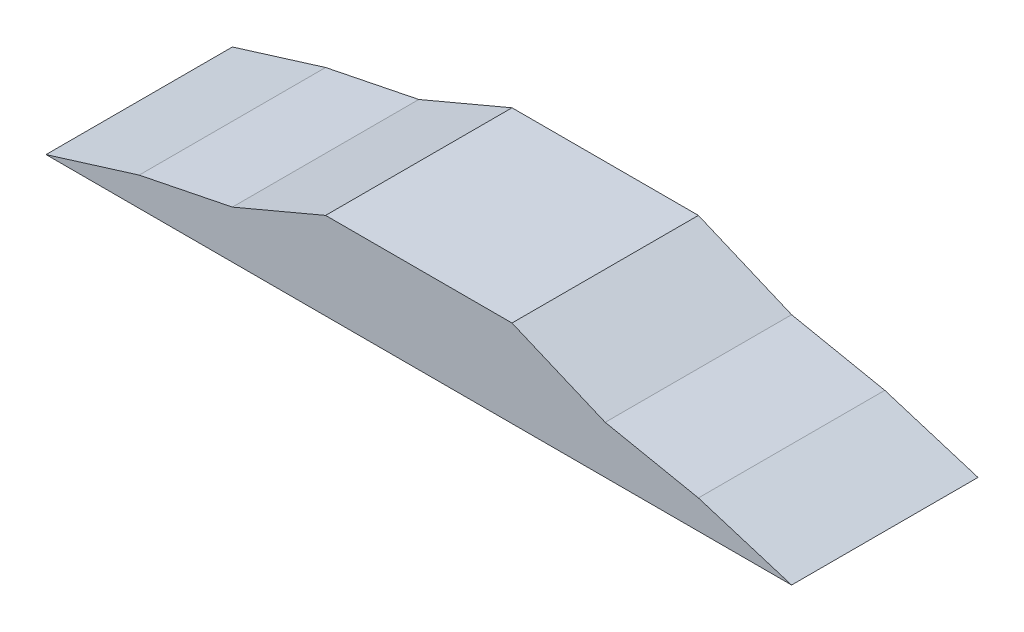
SolidWorks part; units mm, degrees
ref_plane "前视基准面" through (0, 0, 0) normal (0, 0, 1) x (1, 0, 0)
ref_plane "上视基准面" through (0, 0, 0) normal (0, 1, 0) x (1, 0, 0)
ref_plane "右视基准面" through (0, 0, 0) normal (1, 0, 0) x (0, 0, -1)
other "Configuration Table"
sketch "草图1" plane through (0, 0, 0) normal (0, 0, 1) x (1, 0, 0)
  line L0 (0, 0) -> (0, 77.2574) construction
  line L1 (0, 0) -> (-171.8763, 0) construction
  line L11 (-150, 15.4668) -> (-100, 25.6023)
  line L13 (-100, 25.6023) -> (-50, 46.742)
  line L15 (-150, 15.4668) -> (-200, 0)
  line L23 (-50, 46.742) -> (50, 46.742)
  line L24 (-200, 0) -> (200, 0)
  line L25 (0, 0) -> (171.8763, 0) construction
  line L26 (150, 15.4668) -> (200, 0)
  line L27 (100, 25.6023) -> (50, 46.742)
  line L28 (150, 15.4668) -> (100, 25.6023)
  point P8 (0, 0)
  point P14 (0, 0)
  point P16 (0, 46.742)
  point P17 (0, 46.742)
  dimension "D1" = 50
  dimension "D2" = 11.459
  dimension "D3" = 17.189
  dimension "D4" = 50
  dimension "D6" = 50
  dimension "D8" = 50
  dimension "D9" = 22.918
extrude "凸台-拉伸1" add sketch "草图1" along normal blind 100
